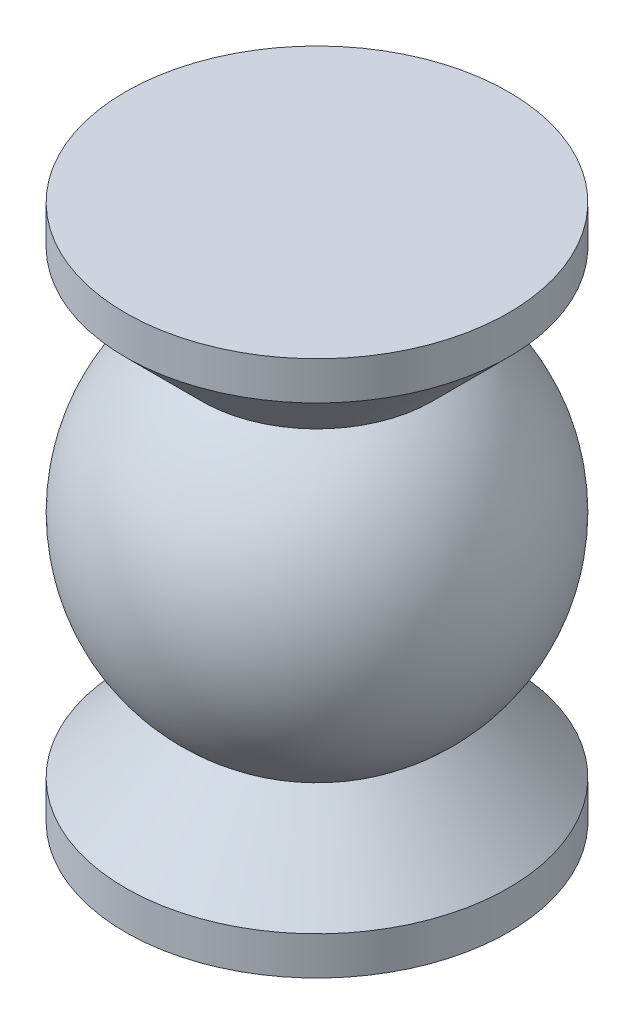
SolidWorks part; units mm, degrees
ref_plane "前视基准面" through (0, 0, 0) normal (0, 0, 1) x (1, 0, 0)
ref_plane "上视基准面" through (0, 0, 0) normal (0, 1, 0) x (1, 0, 0)
ref_plane "右视基准面" through (0, 0, 0) normal (1, 0, 0) x (0, 0, -1)
sketch "草图1" plane through (0, 0, 0) normal (0, 0, 1) x (1, 0, 0)
  line L0 (0, 20) -> (0, -20)
  line L1 (0, 20) -> (15, 20)
  line L2 (15, -20) -> (0, -20)
  arc A0 (15, -20) -> (15, 20) centre (0, 0) ccw
  dimension "D1" = 50
  dimension "D2" = 20
  dimension "D3" = 20
revolve "旋转2" add sketch "草图1" angle 360 about L0
sketch "草图2" plane through (0, 0, 0) normal (0, 0, 1) x (1, 0, 0)
  line L0 (0, 20) -> (15, 20)
  line L1 (15, 20) -> (-15, 20) construction
  line L2 (15, 20) -> (25, 30)
  line L3 (25, 30) -> (25, 35)
  line L4 (25, 35) -> (0, 35)
  line L5 (0, 35) -> (0, 20)
  dimension "D1" = 5
  dimension "D2" = 10
  dimension "D3" = 25
revolve "旋转3" add sketch "草图2" angle 360 about L5
mirror "镜向1" about plane through (0, 0, 0) normal (0, 1, 0) of "旋转3"
